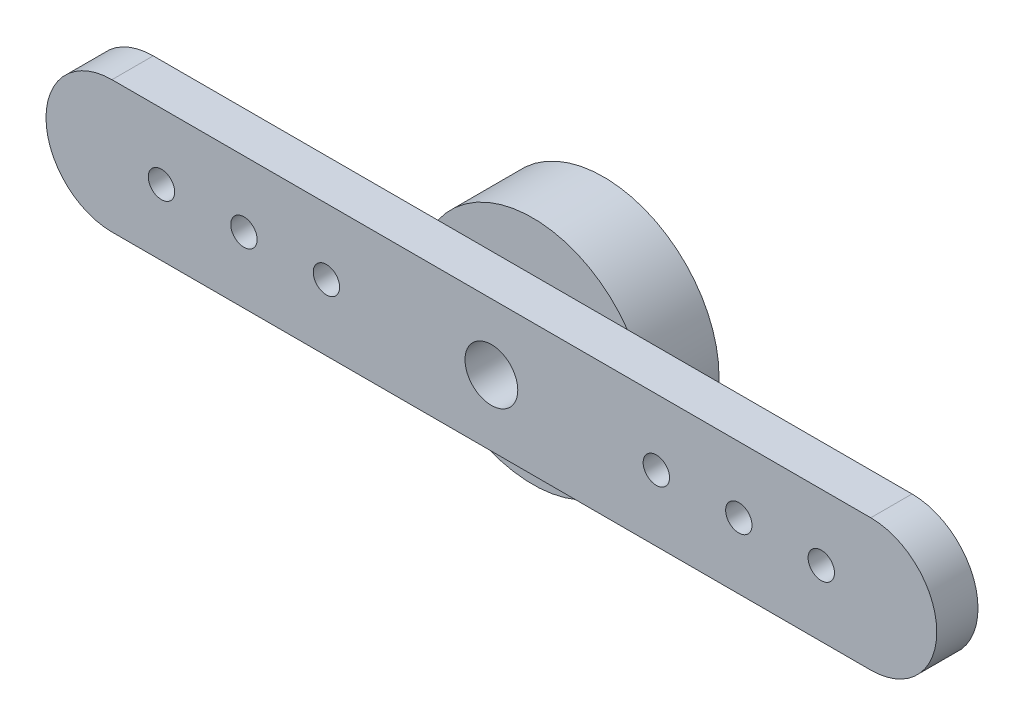
SolidWorks part; units mm, degrees
ref_plane "Front Plane" through (0, 0, 0) normal (0, 0, 1) x (1, 0, 0)
ref_plane "Top Plane" through (0, 0, 0) normal (0, 1, 0) x (1, 0, 0)
ref_plane "Right Plane" through (0, 0, 0) normal (1, 0, 0) x (0, 0, -1)
sketch "Sketch1" plane through (0, 0, 0) normal (0, 0, 1) x (1, 0, 0)
  circle A0 centre (0, 0) radius 7
  circle A1 centre (0, 0) radius 3.05
extrude "Hub" add sketch "Sketch1" along normal blind 4.3 from offset 2.2
sketch "Sketch2" plane through (0, 0, 0) normal (0, 0, 1) x (1, 0, 0)
  line L0 (-23, 4) -> (23, 4)
  line L1 (23, -4) -> (-23, -4)
  arc A0 (23, 4) -> (23, -4) centre (23, 0) cw
  arc A1 (-23, -4) -> (-23, 4) centre (-23, 0) cw
  circle A2 centre (0, 0) radius 1.6
  circle A3 centre (-10, 0) radius 0.8
  circle A4 centre (-15, 0) radius 0.8
  circle A5 centre (-20, 0) radius 0.8
  circle A6 centre (10, 0) radius 0.8
  circle A7 centre (15, 0) radius 0.8
  circle A8 centre (20, 0) radius 0.8
extrude "Arm" add sketch "Sketch2" along normal blind 2.5 from offset 6.5
